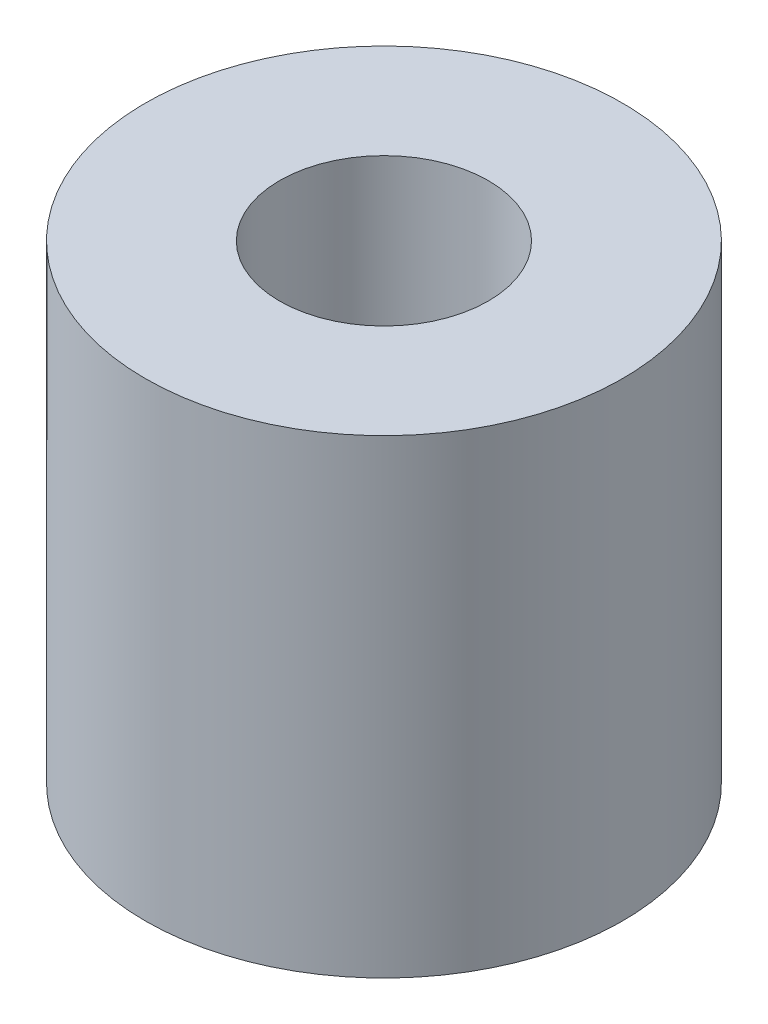
SolidWorks part; units mm, degrees
ref_plane "Front" through (0, 0, 0) normal (0, 0, 1) x (1, 0, 0)
ref_plane "Top" through (0, 0, 0) normal (0, 1, 0) x (1, 0, 0)
ref_plane "Right" through (0, 0, 0) normal (1, 0, 0) x (0, 0, -1)
sketch "Sketch1" plane through (0, 0, 0) normal (0, 1, 0) x (1, 0, 0)
  circle A0 centre (0, 0) radius 2
  circle A1 centre (0, 0) radius 4.572
extrude "Boss-Extrude1" add sketch "Sketch1" along normal blind 9
